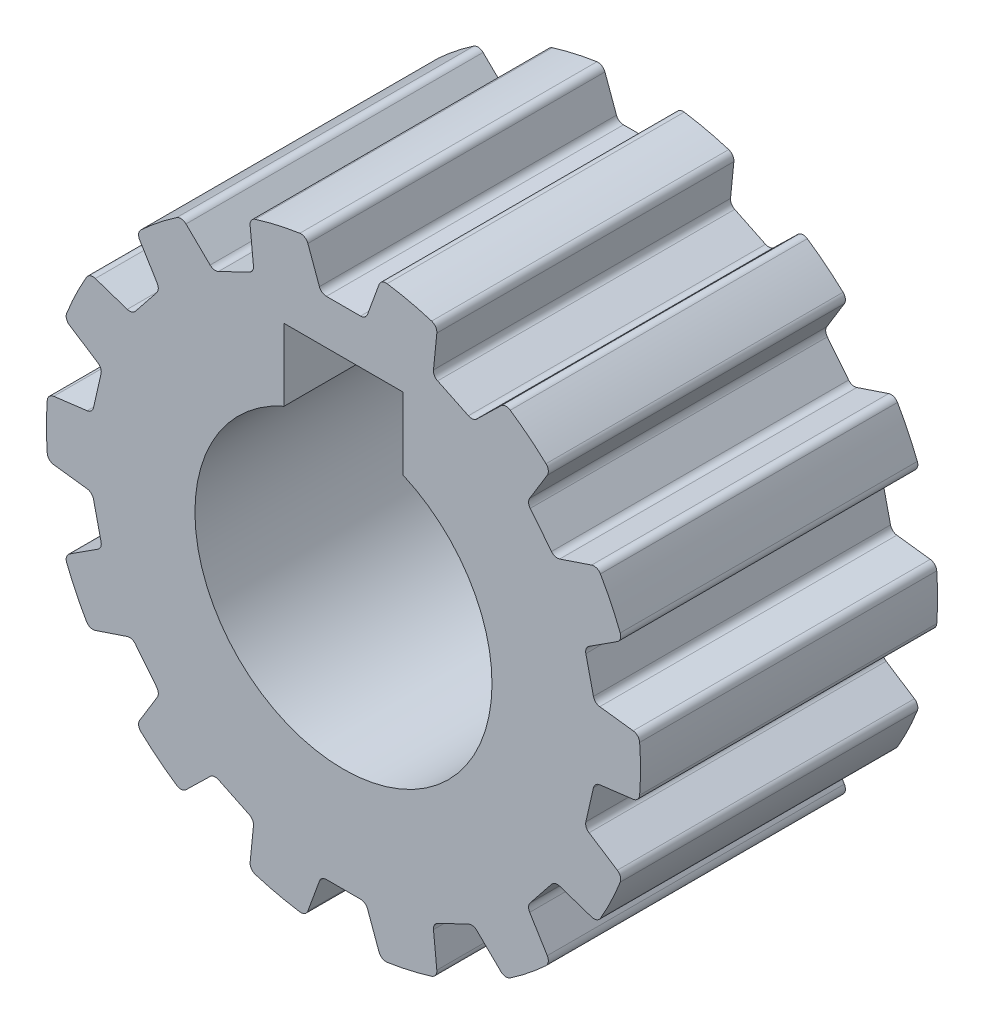
SolidWorks part; units mm, degrees
ref_plane "Front Plane" through (0, 0, 0) normal (0, 0, 1) x (1, 0, 0)
ref_plane "Top Plane" through (0, 0, 0) normal (0, 1, 0) x (1, 0, 0)
ref_plane "Right Plane" through (0, 0, 0) normal (1, 0, 0) x (0, 0, -1)
sketch "Sketch1" plane through (0, 0, 0) normal (0, 0, 1) x (1, 0, 0)
  line L1 (2, 7) -> (-2, 7)
  line L2 (2, 7) -> (2, 4.5826)
  line L4 (-2, 7) -> (-2, 4.5826)
  arc A0 (-2, 4.5826) -> (2, 4.5826) centre (0, 0) ccw
  circle A1 centre (0, 0) radius 10
  point P3 (0, 5)
  dimension "D1" = 10
  dimension "D5" = 20
  dimension "D2" = 4
  dimension "D3" = 7
  dimension "D4" = 2.4174
extrude "Boss-Extrude1" add sketch "Sketch1" along normal mid plane 10
sketch "Sketch2" plane through (0, 0, 5) normal (0, 0, 1) x (1, 0, 0)
  line L0 (0, 0) -> (0, 10) construction
  line L1 (-0.75, 8.5) -> (0.75, 8.5)
  line L2 (0.75, 8.5) -> (1.2666, 9.9195)
  line L3 (-0.75, 8.5) -> (-1.2666, 9.9195)
  circle A0 centre (0, 0) radius 10 construction
  arc A1 (-1.2666, 9.9195) -> (1.2666, 9.9195) centre (0, 9.116) cw
  point P11 (0, 8.5)
  dimension "D3" = 1.5
  dimension "D1" = 0.75
  dimension "D2" = 20
  dimension "D4" = 8.5
extrude "Cut-Extrude1" cut sketch "Sketch2" against normal through all
pattern_circular "CirPattern1" count 14 over 360 about axis through (0, 0, 0) along (0, 0, 1) of "Cut-Extrude1"
fillet "Fillet1" radius 0.25 56 edges at (-7.1132, 4.7133, 0) (-8.5451, 5.1944, 0) (-9.3889, 3.4422, 0) (-8.12, 2.6226, 0) (-8.4538, 1.1602, 0) (-9.9526, 0.9724, 0) (-9.9526, -0.9724, 0) (-8.4538, -1.1602, 0) (-8.12, -2.6226, 0) (-9.3889, -3.4422, 0) (-8.5451, -5.1944, 0) (-7.1132, -4.7133, 0) (-6.178, -5.886, 0) (-6.9656, -7.175, 0) (-5.4451, -8.3875, 0) (-4.3637, -7.3328, 0) (-3.0123, -7.9836, 0) (-3.1627, -9.4867, 0) (-1.2666, -9.9195, 0) (-0.75, -8.5, 0) (0.75, -8.5, 0) (1.2666, -9.9195, 0) (3.1627, -9.4867, 0) (3.0123, -7.9836, 0) (4.3637, -7.3328, 0) (5.4451, -8.3875, 0) (6.9656, -7.175, 0) (6.178, -5.886, 0) (7.1132, -4.7133, 0) (8.5451, -5.1944, 0) (9.3889, -3.4422, 0) (8.12, -2.6226, 0) (8.4538, -1.1602, 0) (9.9526, -0.9724, 0) (9.9526, 0.9724, 0) (8.4538, 1.1602, 0) (8.12, 2.6226, 0) (9.3889, 3.4422, 0) (8.5451, 5.1944, 0) (7.1132, 4.7133, 0) (6.178, 5.886, 0) (6.9656, 7.175, 0) (5.4451, 8.3875, 0) (4.3637, 7.3328, 0) (3.0123, 7.9836, 0) (1.2666, 9.9195, 0) (0.75, 8.5, 0) (-0.75, 8.5, 0) (-1.2666, 9.9195, 0) (-3.1627, 9.4867, 0) (-3.0123, 7.9836, 0) (-4.3637, 7.3328, 0) (-5.4451, 8.3875, 0) (-6.9656, 7.175, 0) (-6.178, 5.886, 0) (3.1627, 9.4867, 0)
